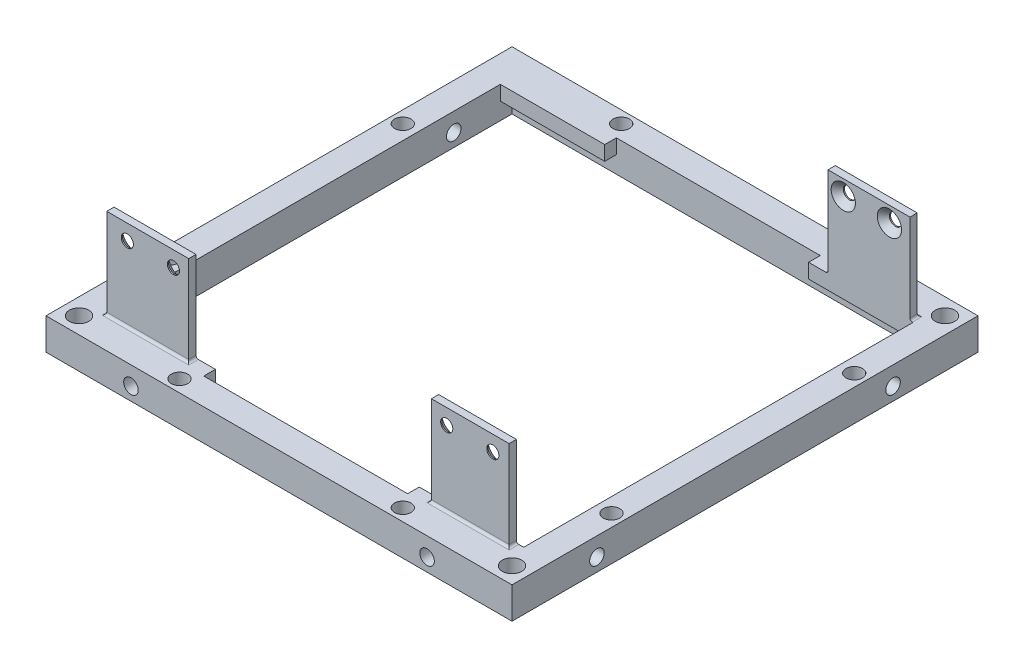
SolidWorks part; units mm, degrees
material "Aluminum"
ref_plane "Front Plane" through (0, 0, 0) normal (0, 0, 1) x (1, 0, 0)
ref_plane "Top Plane" through (0, 0, 0) normal (0, 1, 0) x (1, 0, 0)
ref_plane "Right Plane" through (0, 0, 0) normal (1, 0, 0) x (0, 0, -1)
sketch "Sketch1" plane through (0, 0, 0) normal (0, 1, 0) x (1, 0, 0)
  line L1 (48, -48) -> (-48, -48)
  line L2 (48, -48) -> (48, 48)
  line L3 (48, 48) -> (-48, 48)
  line L4 (-48, -48) -> (-48, 48)
  line L5 (48, -48) -> (-48, 48) construction
  line L6 (48, 48) -> (-48, -48) construction
  line L7 (40, -40) -> (-40, -40)
  line L8 (40, -40) -> (40, 40)
  line L9 (40, 40) -> (-40, 40)
  line L10 (-40, -40) -> (-40, 40)
  line L11 (40, -40) -> (-40, 40) construction
  line L12 (40, 40) -> (-40, -40) construction
  point P0 (0, 0)
  point P6 (0, 0)
  dimension "D1" = 96
  dimension "D2" = 96
  dimension "D3" = 8
extrude "Boss-Extrude1" add sketch "Sketch1" along normal blind 8
hole_wizard "Ø3.0 (3) Diameter Hole3" positions "Sketch10" profile "Sketch9" hole size "Ø3.0" standard "ANSI Metric"
sketch "Sketch10" plane through (0, 0, -48) normal (0, 0, -1) x (-1, 0, 0)
  line L1 (48, 8) -> (48, 0) construction
  point P2 (45, 4)
  dimension "D2" = 3
sketch "Sketch9" plane through (-45, 4, -48) normal (1, 0, 0) x (0, 1, 0)
  line L0 (0, 0) -> (0, 7.5)
  line L1 (0, 7.5) -> (1.5, 7.5)
  line L2 (1.5, 7.5) -> (1.5, 0)
  line L5 (1.5, 0) -> (0, 0)
  line L10 (0, 7.5) -> (-1.5, 7.5) construction
  line L11 (0, -6.35) -> (0, 107.95) construction
  dimension "Hole Dia." = 3
  dimension "Hole Depth" = 7.5
  dimension "Drill Angle" = 180
sketch "Sketch27" plane through (0, 8, 0) normal (0, 1, 0) x (1, 0, 0)
  line L0 (-40, 40) -> (-40, -40) construction
  line L1 (41, -41) -> (-41, -41)
  line L2 (41, -41) -> (41, 41)
  line L3 (41, 41) -> (-41, 41)
  line L4 (-41, -41) -> (-41, 41)
  line L5 (41, -41) -> (-41, 41) construction
  line L6 (41, 41) -> (-41, -41) construction
  line L7 (40, 40) -> (-40, 40) construction
  point P0 (0, 0)
  dimension "D1" = 1
  dimension "D2" = 1
extrude "Cut-Extrude2" cut sketch "Sketch27" against normal blind 10
hole_wizard "Ø3.0 (3) Diameter Hole1" positions "Sketch30" profile "Sketch29" hole size "Ø3.0" standard "ANSI Metric" end condition through all
sketch "Sketch30" plane through (0, 0, 48) normal (0, 0, 1) x (1, 0, 0)
  point P0 (-30.5, 2.7)
  point P4 (30.5, 2.7)
sketch "Sketch29" plane through (-30.5, 2.7, 48) normal (1, 0, 0) x (0, -1, 0)
  line L0 (0, 0) -> (0, 96)
  line L1 (0, 96) -> (1.5, 96)
  line L2 (1.5, 96) -> (1.5, 0)
  line L5 (1.5, 0) -> (0, 0)
  line L11 (0, -6.35) -> (0, 107.95) construction
  dimension "Thru Hole Dia." = 3
  dimension "Thru Hole Depth" = 96
hole_wizard "Ø3.4 (3.4) Diameter Hole1" positions "Sketch37" profile "Sketch36" hole size "Ø3.4" standard "ANSI Metric" end condition through all
sketch "Sketch37" plane through (0, 0, 0) normal (0, -1, 0) x (-1, 0, 0)
  point P0 (-23, 45.5)
  point P2 (23, 45.5)
  point P4 (45.5, 23)
  point P6 (45.5, -25)
  point P8 (23, -45.5)
  point P10 (-23, -45.5)
  point P12 (-45.5, -25)
  point P14 (-45.5, 25)
sketch "Sketch36" plane through (23, 0, -45.5) normal (1, 0, 0) x (0, 0, -1)
  line L0 (0, 0) -> (0, 8)
  line L1 (0, 8) -> (1.7, 8)
  line L2 (1.7, 8) -> (1.7, 0)
  line L5 (1.7, 0) -> (0, 0)
  line L11 (0, -6.35) -> (0, 107.95) construction
  dimension "Thru Hole Dia." = 3.4
  dimension "Thru Hole Depth" = 8
sketch "Sketch38" plane through (0, 8, 0) normal (0, 1, 0) x (1, 0, 0)
  line L0 (48, 48) -> (-48, 48) construction
  line L1 (42.5, -42.5) -> (-42.5, -42.5)
  line L2 (42.5, -42.5) -> (42.5, 42.5)
  line L3 (42.5, 42.5) -> (-42.5, 42.5)
  line L4 (-42.5, -42.5) -> (-42.5, 42.5)
  line L5 (42.5, -42.5) -> (-42.5, 42.5) construction
  line L6 (42.5, 42.5) -> (-42.5, -42.5) construction
  line L7 (-48, 48) -> (-48, -48) construction
  point P0 (0, 0)
  dimension "D1" = 5.5
  dimension "D2" = 5.5
extrude "Cut-Extrude4" cut sketch "Sketch38" against normal blind 10
hole_wizard "Ø3.0 (3) Diameter Hole7" positions "Sketch40" profile "Sketch41" hole size "Ø3.0" standard "ISO" end condition through all
sketch "Sketch40" plane through (-48, 0, 0) normal (-1, 0, 0) x (0, 0, 1)
  point P0 (-30.5, 2.7)
  point P2 (30.5, 2.7)
sketch "Sketch41" plane through (-48, 2.7, -30.5) normal (0, 1, 0) x (0, 0, 1)
  line L0 (0, 0) -> (0, 96)
  line L1 (0, 96) -> (1.5, 96)
  line L2 (1.5, 96) -> (1.5, 0)
  line L5 (1.5, 0) -> (0, 0)
  line L11 (0, -6.35) -> (0, 107.95) construction
  dimension "Thru Hole Dia." = 3
  dimension "Thru Hole Depth" = 96
sketch "Sketch44" plane through (0, 0, 0) normal (0, -1, 0) x (1, 0, 0)
  line L0 (42.5, -42.5) -> (-42.5, -42.5) construction
  line L1 (42.5, -42.5) -> (38.5, -42.5)
  line L2 (42.5, -42.5) -> (42.5, -38.5)
  line L3 (42.5, -38.5) -> (38.5, -38.5)
  line L4 (38.5, -42.5) -> (38.5, -38.5)
  line L5 (42.5, 42.5) -> (42.5, -42.5) construction
  line L6 (0, 0) -> (0, -67.1068) construction
  line L7 (0, 0) -> (66.4168, 0) construction
  line L8 (-38.5, -42.5) -> (-38.5, -38.5)
  line L9 (-42.5, -38.5) -> (-38.5, -38.5)
  line L10 (-42.5, -42.5) -> (-42.5, -38.5)
  line L11 (-42.5, -42.5) -> (-38.5, -42.5)
  line L12 (-42.5, 42.5) -> (-38.5, 42.5)
  line L13 (-42.5, 42.5) -> (-42.5, 38.5)
  line L14 (-42.5, 38.5) -> (-38.5, 38.5)
  line L15 (-38.5, 42.5) -> (-38.5, 38.5)
  line L16 (38.5, 42.5) -> (38.5, 38.5)
  line L17 (42.5, 38.5) -> (38.5, 38.5)
  line L18 (42.5, 42.5) -> (42.5, 38.5)
  line L19 (42.5, 42.5) -> (38.5, 42.5)
  dimension "D1" = 4
  dimension "D2" = 4
extrude "Boss-Extrude2" add sketch "Sketch44" against normal blind 8
sketch "Sketch45" plane through (0, 8, 0) normal (0, 1, 0) x (1, 0, 0)
  line L1 (-42.5, 38.5) -> (-38.5, 38.5)
  line L2 (-42.5, 38.5) -> (-42.5, 35)
  line L3 (-42.5, 35) -> (-38.5, 35)
  line L4 (-38.5, 38.5) -> (-38.5, 35)
  dimension "D1" = 4
  dimension "D2" = 3.5
extrude "Boss-Extrude3" add sketch "Sketch45" against normal blind 8
sketch "Sketch49" plane through (48, 0, 0) normal (1, 0, 0) x (0, 0, -1)
  line L0 (48, 8) -> (48, 0) construction
  line L1 (-48, 8) -> (48, 8)
  line L2 (-48, 8) -> (-48, 6.5)
  line L3 (-48, 6.5) -> (48, 6.5)
  line L4 (48, 8) -> (48, 6.5)
  dimension "D1" = 1.5
extrude "Cut-Extrude5" cut sketch "Sketch49" against normal blind 146
hole_wizard "Tap Drill for M4 Tap1" positions "Sketch51" profile "Sketch50" hole size "M4" standard "ISO" end condition through all
sketch "Sketch51" plane through (0, 6.5, 0) normal (0, 1, 0) x (1, 0, 0)
  line L1 (-48, -48) -> (48, -48) construction
  line L2 (48, -48) -> (48, 48) construction
  line L3 (-48, -48) -> (-48, 48) construction
  line L4 (-48, 48) -> (48, 48) construction
  point P0 (44.6, -44.6)
  point P4 (-44.6, -44.6)
  point P6 (44.6, 44.6)
  dimension "D1" = 3.4
  dimension "D2" = 3.4
  dimension "D3" = 3.4
  dimension "D4" = 3.4
  dimension "D5" = 3.4
  dimension "D6" = 3.4
sketch "Sketch50" plane through (44.6, 6.5, 44.6) normal (1, 0, 0) x (0, 0, 1)
  line L0 (0, 0) -> (0, 6.5)
  line L1 (0, 6.5) -> (2, 6.5)
  line L2 (2, 6.5) -> (2, 0)
  line L5 (2, 0) -> (0, 0)
  line L11 (0, -6.35) -> (0, 107.95) construction
  dimension "Thru Hole Dia." = 4
  dimension "Thru Hole Depth" = 6.5
sketch "Sketch53" plane through (-38.5, 0, 0) normal (1, 0, 0) x (0, 0, -1)
  line L1 (-42.5, 6.5) -> (-38.5, 6.5)
  line L2 (-42.5, 6.5) -> (-42.5, 0)
  line L3 (-42.5, 0) -> (-38.5, 0)
  line L4 (-38.5, 6.5) -> (-38.5, 0)
extrude "Boss-Extrude5" add sketch "Sketch53" along normal blind 78
sketch "Sketch54" plane through (0, 6.5, 0) normal (0, 1, 0) x (1, 0, 0)
  line L0 (42.5, -38.5) -> (-42.5, -38.5) construction
  line L1 (41, -40.099) -> (25, -40.099)
  line L2 (41, -40.099) -> (41, -41.599)
  line L3 (41, -41.599) -> (25, -41.599)
  line L4 (25, -40.099) -> (25, -41.599)
  line L5 (-42.5, 35) -> (-42.5, -38.5) construction
  line L6 (0, -38.5) -> (0, -84.4574) construction
  line L7 (-25, -40.099) -> (-25, -41.599)
  line L8 (-41.8835, -41.599) -> (-25, -41.599)
  line L9 (-41.8835, -40.099) -> (-41.8835, -41.599)
  line L10 (-41.8835, -40.099) -> (-25, -40.099)
  line L11 (0, 0) -> (25.8217, 0) construction
  line L12 (25, 40.099) -> (25, 41.599)
  line L13 (41.8835, 41.599) -> (25, 41.599)
  line L14 (41.8835, 40.099) -> (41.8835, 41.599)
  line L15 (41.8835, 40.099) -> (25, 40.099)
  line L17 (42.5, -38.5) -> (42.5, 38.5) construction
  dimension "D1" = 1.5
  dimension "D2" = 16
  dimension "D3" = 1.5
  dimension "D4" = 0.6165
  dimension "D5" = 1.599
extrude "Boss-Extrude6" add sketch "Sketch54" along normal blind 18.5
fillet "Fillet1" radius 0.5 6 edges at (41, 6.5, 40.849) (33, 6.5, 41.599) (25, 6.5, 40.849) (-25, 6.5, 40.849) (-33.4417, 6.5, 41.599) (-41.8835, 6.5, 40.849)
sketch "Sketch57" plane through (0, 0, -35) normal (0, 0, 1) x (1, 0, 0)
  line L1 (-42.5, 6.5) -> (-38.5, 6.5)
  line L2 (-42.5, 6.5) -> (-42.5, 0)
  line L3 (-42.5, 0) -> (-38.5, 0)
  line L4 (-38.5, 6.5) -> (-38.5, 0)
extrude "Cut-Extrude6" cut sketch "Sketch57" against normal blind 7.5
sketch "Sketch58" plane through (38.5, 0, 0) normal (-1, 0, 0) x (0, 0, 1)
  line L1 (-42.5, 6.5) -> (-38.5, 6.5)
  line L2 (-42.5, 6.5) -> (-42.5, 0)
  line L3 (-42.5, 0) -> (-38.5, 0)
  line L4 (-38.5, 6.5) -> (-38.5, 0)
extrude "Boss-Extrude7" add sketch "Sketch58" along normal blind 81
fillet "Fillet2" radius 0.5 3 edges at (41.8835, 6.5, -40.849) (33.4417, 6.5, -41.599) (25, 6.5, -40.849)
sketch "Sketch61" plane through (0, 6.5, 0) normal (0, 1, 0) x (1, 0, 0)
  line L0 (-48, 48) -> (48, 48) construction
  line L1 (-16, 42.5) -> (16, 42.5)
  line L2 (-16, 42.5) -> (-16, -42.5)
  line L3 (-16, -42.5) -> (16, -42.5)
  line L4 (16, 42.5) -> (16, -42.5)
  line L5 (-48, -48) -> (48, -48) construction
  dimension "D1" = 5.5
  dimension "D2" = 5.5
  dimension "D3" = 16
  dimension "D4" = 16
extrude "Cut-Extrude7" cut sketch "Sketch61" against normal blind 81
hole_wizard "CSK for M2.5 Countersunk Flat Head Screw2" positions "Sketch63" profile "Sketch62" countersink size "M2.5" standard "ISO"
sketch "Sketch63" plane through (0, 0, -40.099) normal (0, 0, 1) x (1, 0, 0)
  point P0 (28.15, 21.8253)
  point P3 (37.65, 21.8253)
sketch "Sketch62" plane through (28.15, 21.8253, -40.099) normal (1, 0, 0) x (0, -1, 0)
  line L0 (0, 0) -> (0, 7.901)
  line L1 (0, 7.901) -> (1.25, 7.901)
  line L2 (1.25, 7.901) -> (1.25, 1.25)
  line L3 (1.25, 1.25) -> (2.5, 0)
  line L5 (2.5, 0) -> (0, 0)
  line L6 (-1.25, 1.25) -> (-2.5, 0) construction
  line L11 (0, -6.35) -> (0, 107.95) construction
  dimension "Thru Hole Dia." = 2.5
  dimension "Thru Hole Depth" = 7.901
  dimension "Near C'Sink Dia." = 5
  dimension "Near C'Sink Angle" = 90
hole_wizard "CSK for M2.5 Countersunk Flat Head Screw1" positions "Sketch65" profile "Sketch64" countersink size "M2.5" standard "ISO"
sketch "Sketch65" plane through (0, 0, 40.099) normal (0, 0, -1) x (-1, 0, 0)
  point P0 (-28.15, 21.8253)
  point P3 (-37.65, 21.8253)
  point P6 (28.15, 21.8253)
  point P9 (37.65, 21.8253)
sketch "Sketch64" plane through (28.15, 21.8253, 40.099) normal (1, 0, 0) x (0, 1, 0)
  line L0 (0, 0) -> (0, 7.901)
  line L1 (0, 7.901) -> (1.25, 7.901)
  line L2 (1.25, 7.901) -> (1.25, 1.25)
  line L3 (1.25, 1.25) -> (2.5, 0)
  line L5 (2.5, 0) -> (0, 0)
  line L6 (-1.25, 1.25) -> (-2.5, 0) construction
  line L11 (0, -6.35) -> (0, 107.95) construction
  dimension "Thru Hole Dia." = 2.5
  dimension "Thru Hole Depth" = 7.901
  dimension "Near C'Sink Dia." = 5
  dimension "Near C'Sink Angle" = 90
sketch "Sketch66" plane through (0, 6.5, 0) normal (0, 1, 0) x (1, 0, 0)
  line L0 (42.5, -38.5) -> (42.5, 38.5) construction
  line L1 (42.5, 40.099) -> (-42.5, 40.099)
  line L2 (42.5, 40.099) -> (42.5, -40.099)
  line L3 (42.5, -40.099) -> (-42.5, -40.099)
  line L4 (-42.5, 40.099) -> (-42.5, -40.099)
  line L5 (-42.5, 38.5) -> (-42.5, -38.5) construction
extrude "Cut-Extrude8" cut sketch "Sketch66" against normal blind 10
sketch "Sketch67" plane through (0, 0, 0) normal (0, -1, 0) x (1, 0, 0)
  line L0 (42.5, 40.099) -> (42.5, -40.099) construction
  line L1 (-42.5, 42.5) -> (42.5, 42.5)
  line L2 (-42.5, 42.5) -> (-42.5, -42.5)
  line L3 (-42.5, -42.5) -> (42.5, -42.5)
  line L4 (42.5, 42.5) -> (42.5, -42.5)
  line L5 (-16, 42.5) -> (16, 42.5) construction
  line L6 (-42.5, -40.099) -> (-42.5, 40.099) construction
  line L7 (16, -42.5) -> (-16, -42.5) construction
extrude "Cut-Extrude9" cut sketch "Sketch67" against normal blind 3.5
sketch "Sketch68" plane through (0, 6.5, 0) normal (0, 1, 0) x (1, 0, 0)
  line L0 (16, -42.5) -> (16, -40.099) construction
  line L1 (21, 42.5) -> (-21, 42.5)
  line L2 (21, 42.5) -> (21, -42.5)
  line L3 (21, -42.5) -> (-21, -42.5)
  line L4 (-21, 42.5) -> (-21, -42.5)
  point P4 (16, -41.2995)
  dimension "D1" = 5
  dimension "D2" = 5
extrude "Cut-Extrude10" cut sketch "Sketch68" against normal blind 56
